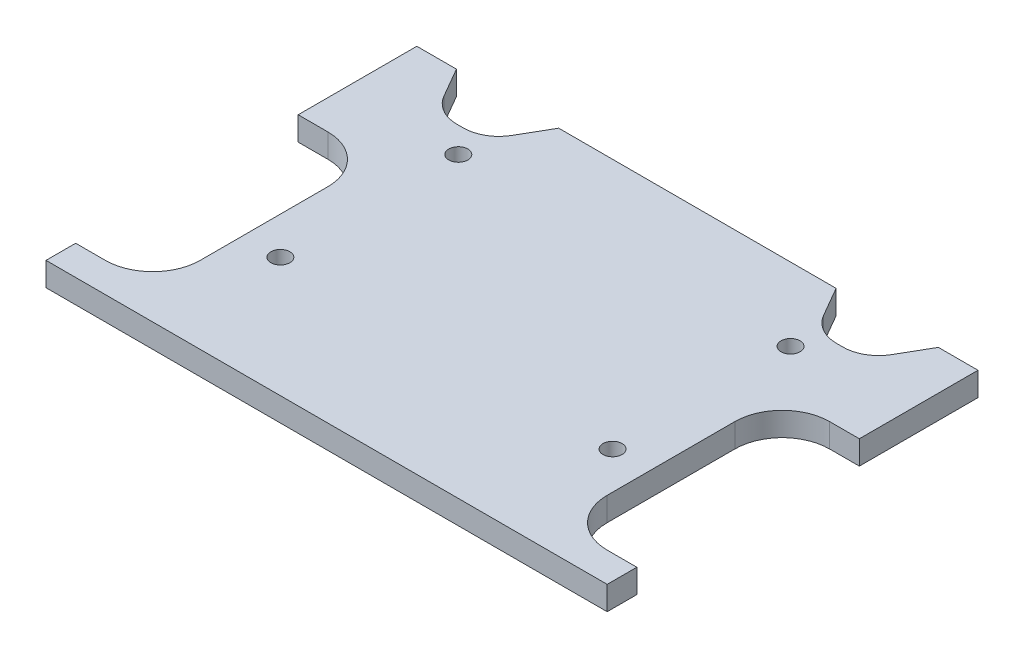
SolidWorks part; units mm, degrees
material "Custom Plastic"
ref_plane "Front" through (0, 0, 0) normal (0, 0, 1) x (1, 0, 0)
ref_plane "Top" through (0, 0, 0) normal (0, 1, 0) x (1, 0, 0)
ref_plane "Right" through (0, 0, 0) normal (1, 0, 0) x (0, 0, -1)
sketch "Sketch1" plane through (0, 0, 0) normal (0, 1, 0) x (1, 0, 0)
  line L0 (-54.448, -16.6673) -> (-54.448, -50.8129)
  line L1 (-75.0855, 27.7827) -> (-64.4823, 27.7827)
  line L2 (-75.0855, 27.7827) -> (-75.0855, -3.9673)
  line L3 (-75.0855, -3.9673) -> (-67.148, -3.9673)
  line L4 (75.0855, 27.7827) -> (75.0855, -3.9673)
  line L5 (-64.4823, 27.7827) -> (-59.8996, 19.8452)
  line L6 (71.9105, 27.7827) -> (75.0855, 27.7827) construction
  line L7 (-75.0855, -71.4504) -> (75.0855, -71.4504)
  line L8 (71.9105, -3.9673) -> (75.0855, -3.9673) construction
  line L9 (54.448, -50.8129) -> (54.448, -16.6673)
  line L10 (67.148, -3.9673) -> (75.0855, -3.9673)
  line L11 (64.4823, 27.7827) -> (75.0855, 27.7827)
  line L14 (-51.6507, 15.0827) -> (-49.9493, 15.0827)
  line L18 (49.9493, 15.0827) -> (51.6507, 15.0827)
  line L20 (-37.1177, 27.7827) -> (37.1177, 27.7827)
  line L21 (75.0855, -0.7923) -> (75.0855, -3.9673) construction
  line L22 (-41.7004, 19.8452) -> (-37.1177, 27.7827)
  line L23 (37.1177, 27.7827) -> (41.7004, 19.8452)
  line L24 (59.8996, 19.8452) -> (64.4823, 27.7827)
  line L25 (71.9105, -71.4504) -> (75.0855, -71.4504) construction
  line L26 (75.0855, -71.4504) -> (75.0855, -63.5129)
  line L27 (75.0855, -63.5129) -> (67.148, -63.5129)
  line L28 (75.0855, -69.8629) -> (75.0855, -73.0379) construction
  line L29 (71.9105, -63.5129) -> (75.0855, -63.5129) construction
  line L31 (-67.148, -63.5129) -> (-75.0855, -63.5129)
  line L32 (-75.0855, -63.5129) -> (-75.0855, -71.4504)
  arc A0 (67.148, -3.9673) -> (54.448, -16.6673) centre (67.148, -16.6673) ccw
  arc A1 (-54.448, -16.6673) -> (-67.148, -3.9673) centre (-67.148, -16.6673) ccw
  arc A2 (-67.148, -63.5129) -> (-54.448, -50.8129) centre (-67.148, -50.8129) ccw
  arc A3 (-49.9493, 15.0827) -> (-41.7004, 19.8452) centre (-49.9493, 24.6077) ccw
  arc A4 (-59.8996, 19.8452) -> (-51.6507, 15.0827) centre (-51.6507, 24.6077) ccw
  arc A5 (51.6507, 15.0827) -> (59.8996, 19.8452) centre (51.6507, 24.6077) ccw
  arc A6 (41.7004, 19.8452) -> (49.9493, 15.0827) centre (49.9493, 24.6077) ccw
  arc A7 (67.148, -63.5129) -> (54.448, -50.8129) centre (67.148, -50.8129) cw
  point P18 (0, 27.7827)
  point P29 (-54.448, -3.9673)
  point P30 (50.8, 15.0827)
  point P42 (57.15, 15.0827)
  point P45 (44.45, 15.0827)
  dimension "D3" = 12.7
  dimension "D7" = 9.525
  dimension "D2" = 12.7
  dimension "D1" = 20.6375
  dimension "D4" = 60
  dimension "D5" = 12.7
  dimension "D6" = 12.7
extrude "Boss-Extrude1" add sketch "Sketch1" along normal blind 6.35
hole_wizard "#10 Clearance Hole1" positions "Sketch2" profile "Sketch3" hole size "#10" standard "ANSI Inch" end condition through all
sketch "Sketch2" plane through (0, 6.35, 0) normal (0, 1, 0) x (1, 0, 0)
  arc A0 (44.0407, 10.7715) -> (46.9697, 7.8425) centre (44.45, 8.2519) ccw construction
  arc A1 (-46.9697, 7.8425) -> (-44.0407, 10.7715) centre (-44.45, 8.2519) ccw construction
  arc A2 (46.9697, -38.9638) -> (44.0407, -41.8928) centre (44.45, -39.3731) ccw construction
  arc A3 (-44.0407, -41.8928) -> (-46.9697, -38.9638) centre (-44.45, -39.3731) ccw construction
  point P0 (-44.45, 8.2519)
  point P2 (-44.45, -39.3731)
  point P4 (44.45, 8.2519)
  point P6 (44.45, -39.3731)
  point P32 (0, 0)
  point P33 (0, 0)
sketch "Sketch3" plane through (-44.45, 6.35, -8.2519) normal (1, 0, 0) x (0, 0, 1)
  line L0 (0, 0) -> (0, 6.35)
  line L1 (0, 6.35) -> (2.5527, 6.35)
  line L2 (2.5527, 6.35) -> (2.5527, 0)
  line L5 (2.5527, 0) -> (0, 0)
  line L11 (0, -6.35) -> (0, 107.95) construction
  dimension "Thru Hole Dia." = 5.1054
  dimension "Thru Hole Depth" = 6.35
